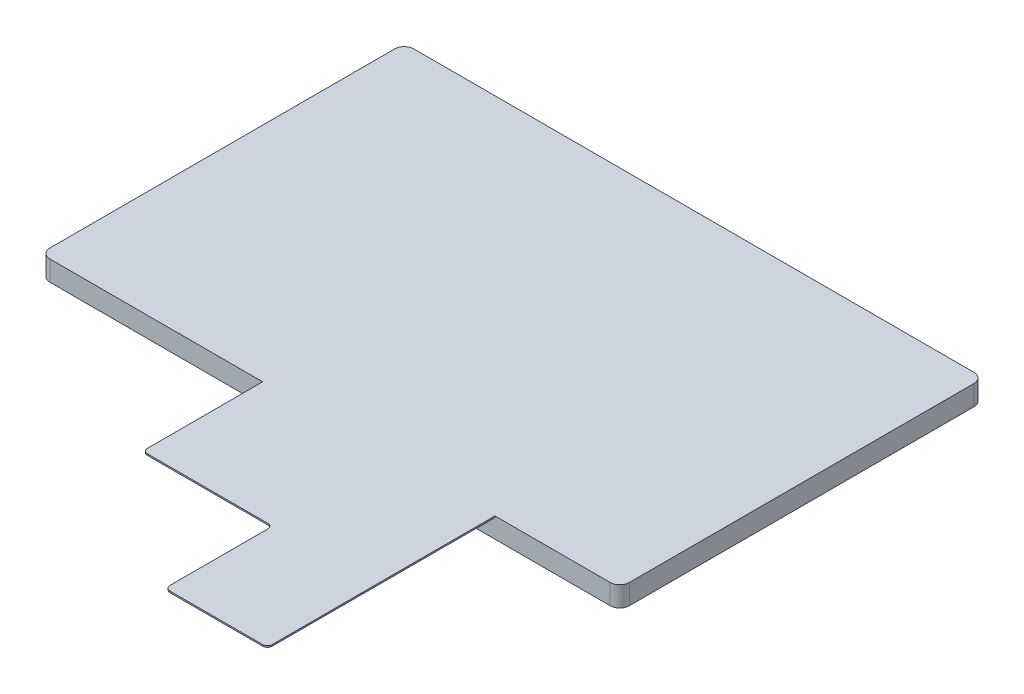
SolidWorks part; units mm, degrees
ref_plane "Front Plane" through (0, 0, 0) normal (0, 0, 1) x (1, 0, 0)
ref_plane "Top Plane" through (0, 0, 0) normal (0, 1, 0) x (1, 0, 0)
ref_plane "Right Plane" through (0, 0, 0) normal (1, 0, 0) x (0, 0, -1)
sketch "Sketch1" plane through (0, 0, 0) normal (0, 1, 0) x (1, 0, 0)
  line L1 (0, 0) -> (120.7, 0)
  line L2 (0, 0) -> (0, -75.8)
  line L3 (0, -75.8) -> (120.7, -75.8)
  line L4 (120.7, 0) -> (120.7, -75.8)
  dimension "D1" = 75.8
  dimension "D2" = 120.7
extrude "Boss-Extrude1" add sketch "Sketch1" along normal blind 4.2
sketch "Sketch2" plane through (0, 4.2, 0) normal (0, 1, 0) x (1, 0, 0)
  line L0 (0, -75.8) -> (120.7, -75.8) construction
  line L1 (46.3, -75.8) -> (94.7, -75.8)
  line L2 (46.3, -75.8) -> (46.3, -123.2)
  line L3 (46.3, -123.2) -> (94.7, -123.2)
  line L4 (94.7, -75.8) -> (94.7, -123.2)
  line L6 (120.7, -75.8) -> (120.7, 0) construction
  dimension "D2" = 47.4
  dimension "D3" = 48.4
  dimension "D1" = 26
extrude "Boss-Extrude2" add sketch "Sketch2" against normal blind 0.3
sketch "Sketch4" plane through (0, 3.9, 0) normal (0, -1, 0) x (1, 0, 0)
  line L1 (46.3, 123.2) -> (73.38, 123.2)
  line L2 (46.3, 123.2) -> (46.3, 100.79)
  line L3 (46.3, 100.79) -> (73.38, 100.79)
  line L4 (73.38, 123.2) -> (73.38, 100.79)
  dimension "D1" = 27.08
  dimension "D2" = 22.41
extrude "Cut-Extrude1" cut sketch "Sketch4" against normal blind 0.3
fillet "Fillet2" radius 1 4 edges at (46.3, 4.05, 100.79) (73.38, 4.05, 100.79) (73.38, 4.05, 123.2) (94.7, 4.05, 123.2)
fillet "Fillet3" radius 2 4 edges at (120.7, 2.1, 75.8) (0, 2.1, 75.8) (120.7, 2.1, 0) (0, 2.1, 0)
sketch "Sketch5" plane through (0, 0, 0) normal (0, -1, 0) x (-1, 0, 0)
  text T0 "<b>DISPLAY SCREEN</b>"
equation "\"D3@Sketch2\"=20.5+27.9"
